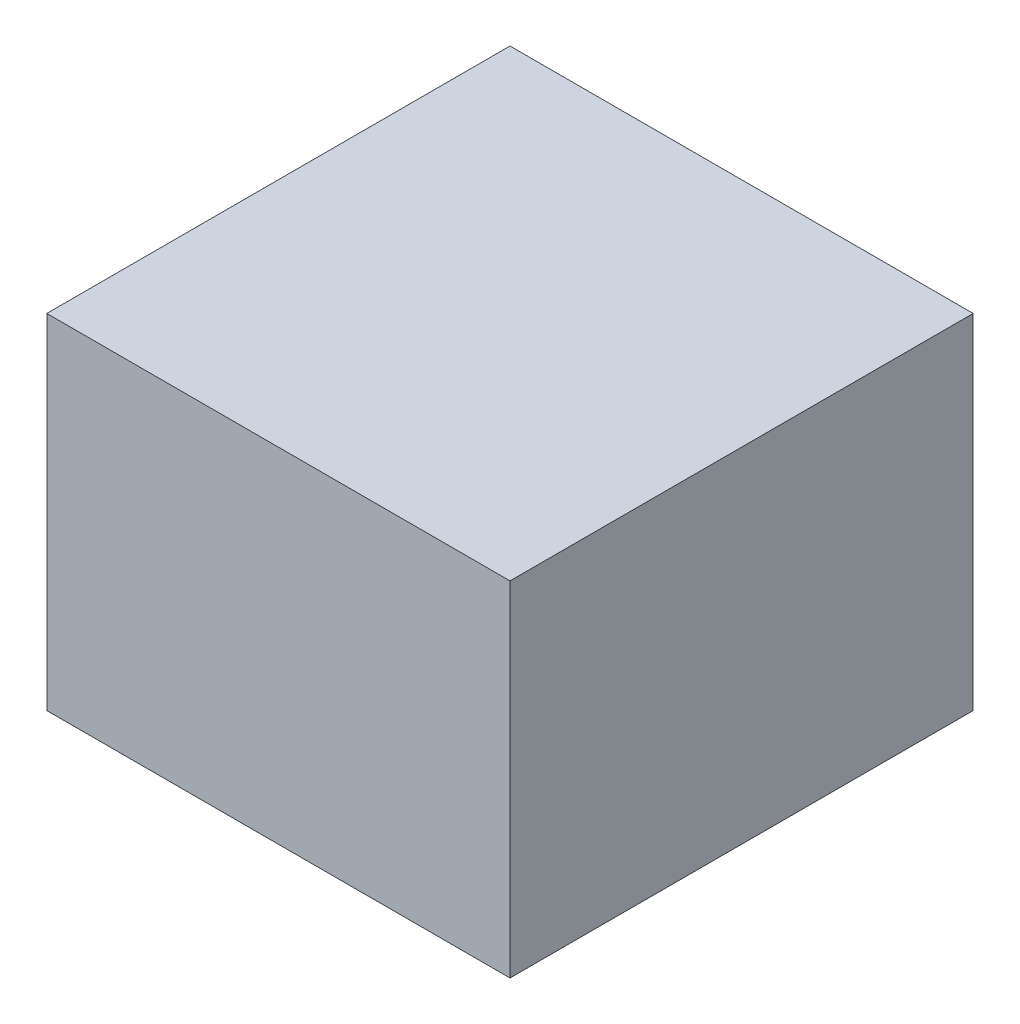
SolidWorks part; units mm, degrees
ref_plane "Front Plane" through (0, 0, 0) normal (0, 0, 1) x (1, 0, 0)
ref_plane "Top Plane" through (0, 0, 0) normal (0, 1, 0) x (1, 0, 0)
ref_plane "Right Plane" through (0, 0, 0) normal (1, 0, 0) x (0, 0, -1)
sketch "Sketch1" plane through (0, 0, 0) normal (0, 1, 0) x (1, 0, 0)
  line L1 (-372.6826, 278.0212) -> (219.1374, 278.0212)
  line L2 (-372.6826, 278.0212) -> (-372.6826, -313.7988)
  line L3 (-372.6826, -313.7988) -> (219.1374, -313.7988)
  line L4 (219.1374, 278.0212) -> (219.1374, -313.7988)
  dimension "D1" = 591.82
  dimension "D2" = 591.82
extrude "Boss-Extrude1" add sketch "Sketch1" along normal blind 439.42
